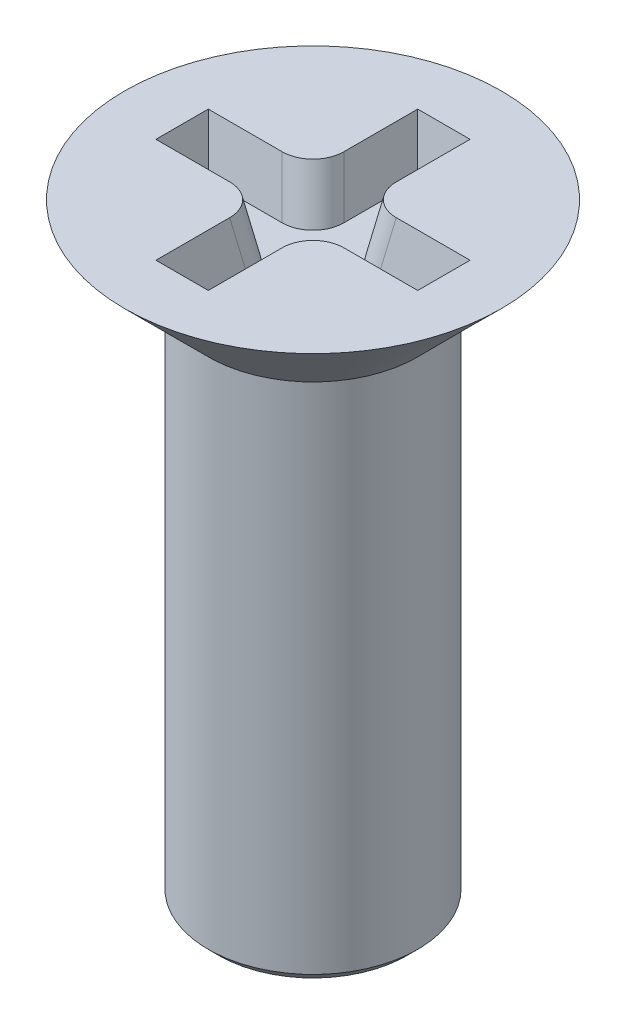
SolidWorks part; units mm, degrees
material "AISI 321 退火不锈钢 (SS)"
ref_plane "前视基准面" through (0, 0, 0) normal (0, 0, 1) x (1, 0, 0)
ref_plane "上视基准面" through (0, 0, 0) normal (0, 1, 0) x (1, 0, 0)
ref_plane "右视基准面" through (0, 0, 0) normal (1, 0, 0) x (0, 0, -1)
other "Configuration Table"
sketch "草图1" plane through (0, 0, 0) normal (0, 0, 1) x (1, 0, 0)
  line L0 (0, 0) -> (1.8, 0)
  line L1 (1.8, 0) -> (1, -0.8)
  line L2 (1, -0.8) -> (0, -0.8)
  line L3 (0, -0.8) -> (0, 0)
  dimension "D1" = 1.8
  dimension "D2" = 0.8
  dimension "D3" = 1
revolve "旋转1" add sketch "草图1" angle 360 about L3
sketch "草图2" plane through (0, -0.8, 0) normal (0, -1, 0) x (1, 0, 0)
  circle A1 centre (0, 0) radius 1
  circle A2 centre (0, 0) radius 1
  dimension "D1" = 0
extrude "凸台-拉伸1" add sketch "草图2" along normal blind 5
cosmetic thread "装饰螺纹线2" parameters "D2"=1.567
sketch "草图3" plane through (0, 0, 0) normal (0, 1, 0) x (1, 0, 0)
  line L1 (-1.25, -0.25) -> (1.25, -0.25)
  line L2 (-1.25, -0.25) -> (-1.25, 0.25)
  line L3 (-1.25, 0.25) -> (1.25, 0.25)
  line L4 (1.25, -0.25) -> (1.25, 0.25)
  line L5 (-1.25, -0.25) -> (1.25, 0.25) construction
  line L6 (-1.25, 0.25) -> (1.25, -0.25) construction
  line L7 (-0.25, 1.25) -> (0.25, 1.25)
  line L8 (-0.25, 1.25) -> (-0.25, -1.25)
  line L9 (-0.25, -1.25) -> (0.25, -1.25)
  line L10 (0.25, 1.25) -> (0.25, -1.25)
  line L11 (-0.25, 1.25) -> (0.25, -1.25) construction
  line L12 (-0.25, -1.25) -> (0.25, 1.25) construction
  point P0 (0, 0)
  point P6 (0, 0)
  dimension "D1" = 0.5
  dimension "D2" = 0.5
  dimension "D3" = 2.5
  dimension "D4" = 2.5
extrude "切除-拉伸1" cut sketch "草图3" against normal blind 0.5 draft 10 contours L3 L10 L1 L4 | L10 L7 L8 L3 | L8 L3 L2 L1 | L10 L3 L8 L1 | L10 L1 L8 L9
fillet "圆角1" radius 0.3 4 edges at (-0.2059, -0.25, -0.2059) (0.2059, -0.25, -0.2059) (-0.2059, -0.25, 0.2059) (0.2059, -0.25, 0.2059)
chamfer "倒角2" distance 0.1 angle 45 1 edges at (0, -5.8, -1)
